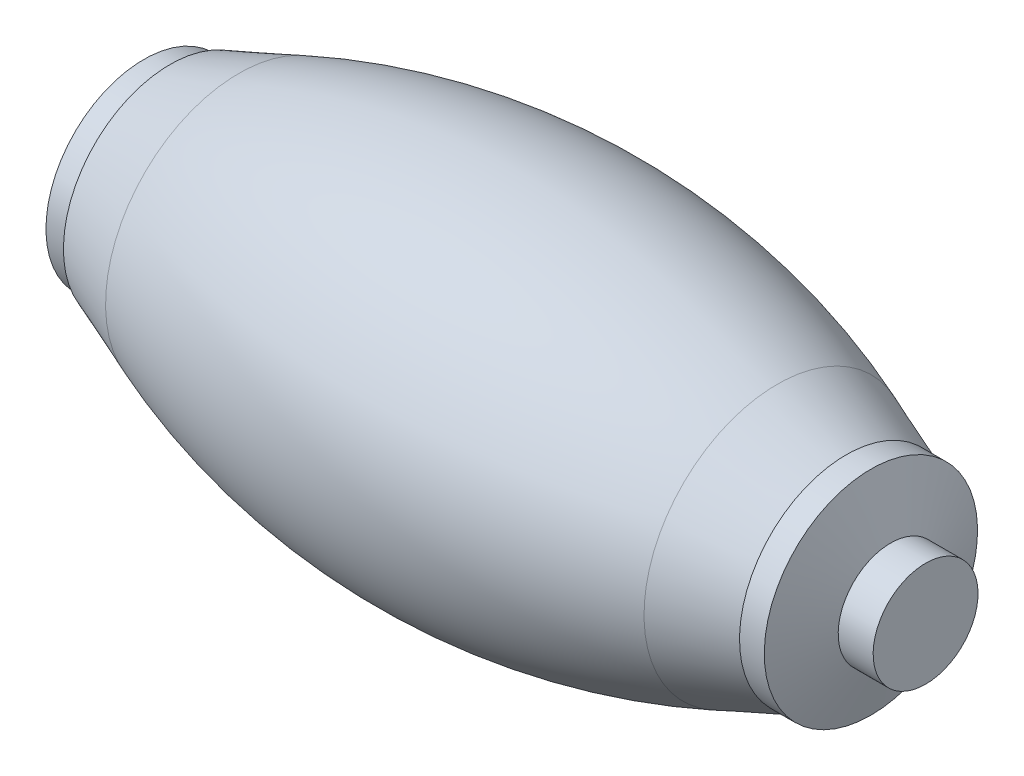
SolidWorks part; units mm, degrees
material "Natural Rubber"
ref_plane "Front Plane" through (0, 0, 0) normal (0, 0, 1) x (1, 0, 0)
ref_plane "Top Plane" through (0, 0, 0) normal (0, 1, 0) x (1, 0, 0)
ref_plane "Right Plane" through (0, 0, 0) normal (1, 0, 0) x (0, 0, -1)
sketch "Sketch1" plane through (0, 0, 0) normal (0, 0, 1) x (1, 0, 0)
  line L0 (-142, 35.56) -> (-132.475, 35.56)
  line L1 (-132.475, 35.56) -> (-132.475, 38.735)
  line L2 (-132.475, 38.735) -> (-104.4743, 66.7357) construction
  line L3 (-104.4743, 66.7357) -> (85.1346, 66.7357) construction
  line L4 (85.1346, 66.7357) -> (113.1352, 38.735) construction
  line L5 (113.1352, 38.735) -> (122.1352, 38.735)
  line L6 (122.1352, 38.735) -> (129.3, 19.05)
  line L7 (129.3, 19.05) -> (142, 19.05)
  line L8 (142, 19.05) -> (142, 0)
  line L9 (142, 0) -> (-142, 0)
  line L10 (-142, 0) -> (-142, 35.56)
  line L11 (142, 0) -> (148.1547, 0) construction
  line L12 (-132.475, 38.735) -> (-107.475, 48.4319)
  line L13 (88.1352, 48.4319) -> (113.1352, 38.735)
  arc A0 (-107.475, 48.4319) -> (88.1352, 48.4319) centre (-9.6699, -203.7241) cw
  point P16 (-9.6699, 66.7357)
  point P17 (0, 0)
  dimension "D1" = 284
  dimension "D2" = 12.7
  dimension "D3" = 38.1
  dimension "D4" = 133.4713
  dimension "D5" = 45
  dimension "D6" = 45
  dimension "D7" = 9
  dimension "D8" = 9.525
  dimension "D9" = 71.12
  dimension "D10" = 3.175
  dimension "D11" = 70
  dimension "D12" = 25
revolve "Revolve1" add sketch "Sketch1" angle 360 about L11
ref_plane "Plane1" through (-9.6699, 0, 0) normal (1, 0, 0) x (0, 0, -1)
